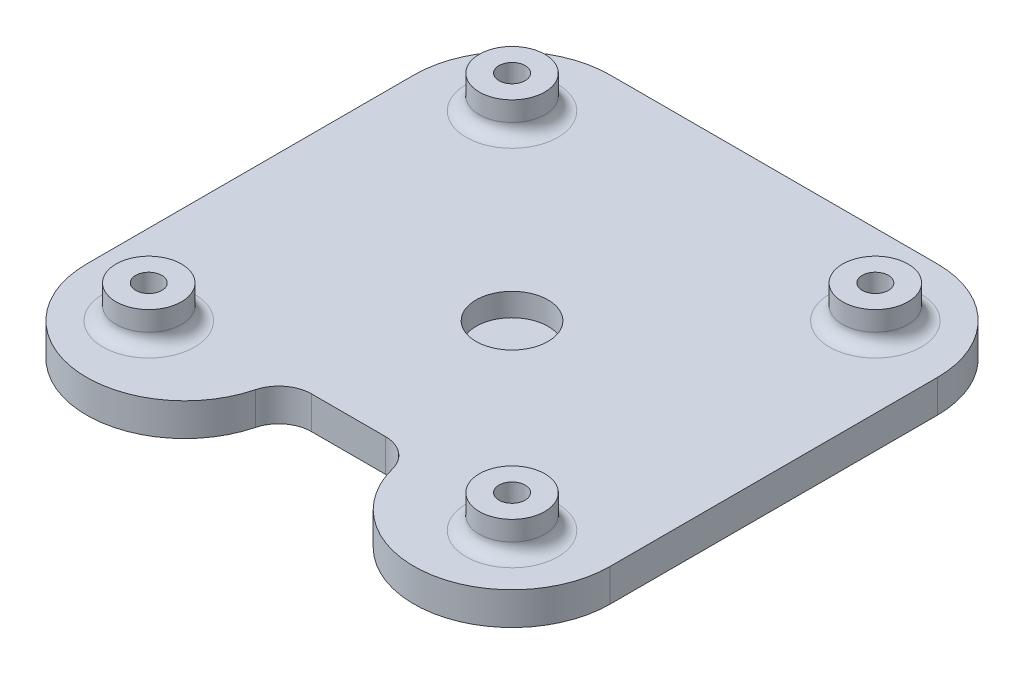
SolidWorks part; units mm, degrees
ref_plane "Front Plane" through (0, 0, 0) normal (0, 0, 1) x (1, 0, 0)
ref_plane "Top Plane" through (0, 0, 0) normal (0, 1, 0) x (1, 0, 0)
ref_plane "Right Plane" through (0, 0, 0) normal (1, 0, 0) x (0, 0, -1)
sketch "Sketch12" plane through (0, 0, 0) normal (0, 1, 0) x (1, 0, 0)
  line L0 (-20, -50) -> (20, -50)
  line L1 (-50, 80) -> (50, 80)
  line L2 (-80, 50) -> (-80, -50)
  line L4 (80, 50) -> (80, -50)
  line L5 (-80, 80) -> (80, -80) construction
  line L6 (-80, -80) -> (80, 80) construction
  arc A0 (50, -80) -> (80, -50) centre (50, -50) ccw
  arc A1 (-80, -50) -> (-50, -80) centre (-50, -50) ccw
  arc A2 (50, 80) -> (80, 50) centre (50, 50) cw
  arc A3 (-50, 80) -> (-80, 50) centre (-50, 50) ccw
  arc A4 (-50, -80) -> (-20, -50) centre (-50, -50) ccw
  arc A5 (50, -80) -> (20, -50) centre (50, -50) cw
  point P0 (0, 0)
  dimension "D1" = 30
extrude "Boss-Extrude6" add sketch "Sketch12" along normal blind 10
fillet "Fillet4" radius 10 2 edges at (20, 5, 50) (-20, 5, 50)
sketch "Sketch13" plane through (0, 10, 0) normal (0, 1, 0) x (1, 0, 0)
  line L1 (-55.5, 55.5) -> (55.5, 55.5) construction
  line L2 (-55.5, 55.5) -> (-55.5, -55.5) construction
  line L3 (-55.5, -55.5) -> (55.5, -55.5) construction
  line L4 (55.5, 55.5) -> (55.5, -55.5) construction
  line L5 (-55.5, 55.5) -> (55.5, -55.5) construction
  line L6 (-55.5, -55.5) -> (55.5, 55.5) construction
  circle A0 centre (-55.5, 55.5) radius 4
  circle A1 centre (55.5, 55.5) radius 4
  circle A2 centre (-55.5, -55.5) radius 4
  circle A3 centre (55.5, -55.5) radius 4
  point P0 (0, 0)
extrude "Cut-Extrude5" cut sketch "Sketch13" against normal through all
sketch "Sketch14" plane through (0, 10, 0) normal (0, 1, 0) x (1, 0, 0)
  circle A2 centre (-55.5, 55.5) radius 10
  circle A3 centre (-55.5, 55.5) radius 10
  circle A8 centre (55.5, 55.5) radius 10
  circle A9 centre (55.5, 55.5) radius 10
  circle A11 centre (-55.5, -55.5) radius 10
  circle A12 centre (-55.5, -55.5) radius 10
  circle A14 centre (55.5, -55.5) radius 10
  circle A15 centre (55.5, -55.5) radius 10
  dimension "D1" = 6
  dimension "D2" = 6
  dimension "D3" = 6
  dimension "D4" = 6
extrude "Boss-Extrude7" add sketch "Sketch14" along normal blind 10
sketch "Sketch15" plane through (0, 10, 0) normal (0, -1, 0) x (1, 0, 0)
  circle A1 centre (-55.5, -55.5) radius 4
  circle A2 centre (-55.5, -55.5) radius 4
  circle A3 centre (-55.5, 55.5) radius 4
  circle A4 centre (-55.5, 55.5) radius 4
  circle A5 centre (55.5, 55.5) radius 4
  circle A6 centre (55.5, 55.5) radius 4
  circle A7 centre (55.5, -55.5) radius 4
  circle A8 centre (55.5, -55.5) radius 4
  dimension "D1" = 0
  dimension "D2" = 0
  dimension "D3" = 0
  dimension "D4" = 0
extrude "Cut-Extrude6" cut sketch "Sketch15" against normal through all
fillet "Fillet5" radius 4 4 edges at (-55.5, 10, -65.5) (55.5, 10, -65.5) (55.5, 10, 45.5) (-55.5, 10, 45.5)
sketch "Sketch16" plane through (0, 10, 0) normal (0, 1, 0) x (1, 0, 0)
  circle A0 centre (0, 0) radius 11
extrude "Cut-Extrude7" cut sketch "Sketch16" against normal blind 7
